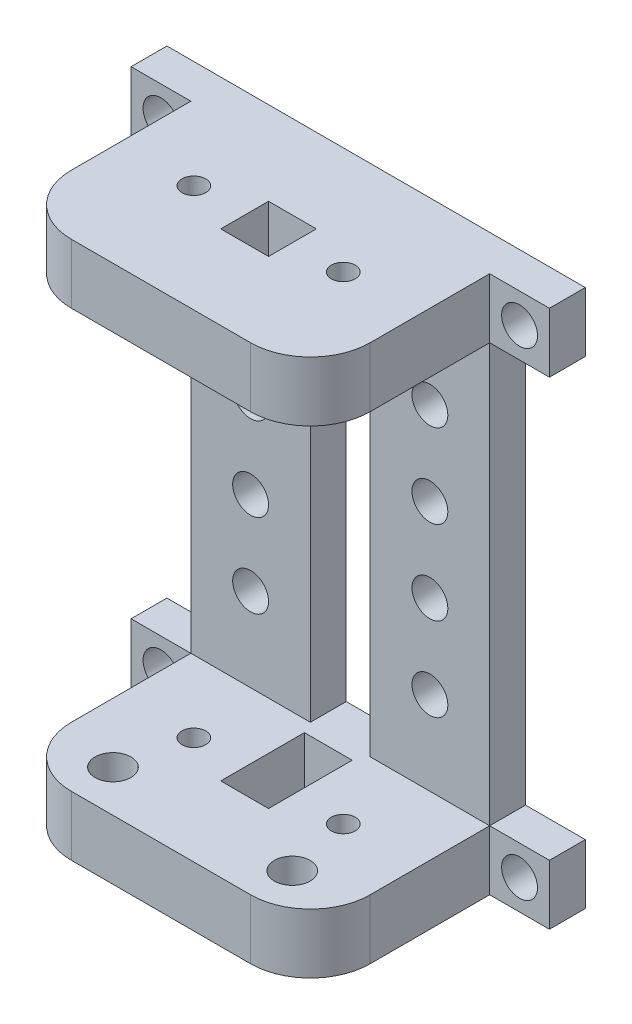
SolidWorks part; units mm, degrees
ref_plane "Plano frontal" through (0, 0, 0) normal (0, 0, 1) x (1, 0, 0)
ref_plane "Plano superior" through (0, 0, 0) normal (0, 1, 0) x (1, 0, 0)
ref_plane "Plano direito" through (0, 0, 0) normal (1, 0, 0) x (0, 0, -1)
sketch "Esboço1" plane through (0, 0, 0) normal (0, 0, 1) x (1, 0, 0)
  line L0 (-24.4304, 7.0667) -> (10.5696, 7.0667)
  line L1 (-24.4304, 7.0667) -> (-24.4304, 2.0667)
  line L2 (10.5696, -37.9333) -> (-24.4304, -37.9333)
  line L3 (-24.4304, 2.0667) -> (-19.4304, 2.0667)
  line L4 (-19.4304, 2.0667) -> (-19.4304, -32.9333)
  line L5 (-19.4304, -32.9333) -> (-24.4304, -32.9333)
  line L6 (-24.4304, -32.9333) -> (-24.4304, -37.9333)
  line L7 (10.5696, -37.9333) -> (10.5696, -32.9333)
  line L8 (10.5696, -32.9333) -> (5.5696, -32.9333)
  line L9 (5.5696, -32.9333) -> (5.5696, 2.0667)
  line L10 (5.5696, 2.0667) -> (10.5696, 2.0667)
  line L11 (10.5696, 2.0667) -> (10.5696, 7.0667)
  line L12 (-9.4304, 2.0667) -> (-9.4304, -32.9333)
  line L13 (-9.4304, -32.9333) -> (-4.4304, -32.9333)
  line L14 (-4.4304, -32.9333) -> (-4.4304, 2.0667)
  line L15 (-4.4304, 2.0667) -> (-9.4304, 2.0667)
  circle A0 centre (-14.4304, -4.9333) radius 1.5
  circle A1 centre (-14.4304, -11.9333) radius 1.5
  circle A2 centre (-14.4304, -18.9333) radius 1.5
  circle A3 centre (0.5696, -4.9333) radius 1.5
  circle A4 centre (0.5696, -18.9333) radius 1.5
  circle A5 centre (0.5696, -25.9333) radius 1.5
  circle A6 centre (-14.4304, -25.9333) radius 1.5
  circle A7 centre (0.5696, -11.9333) radius 1.5
  circle A8 centre (-21.9304, 4.5667) radius 1.5
  circle A9 centre (8.0696, 4.5667) radius 1.5
  circle A10 centre (-21.9304, -35.4333) radius 1.5
  circle A11 centre (8.0696, -35.4333) radius 1.5
  dimension "D13" = 3
  dimension "D1" = 35
  dimension "D2" = 10
  dimension "D3" = 10
  dimension "D4" = 5
  dimension "D5" = 5
  dimension "D6" = 5
  dimension "D7" = 5
  dimension "D8" = 5
  dimension "D9" = 5
  dimension "D10" = 5
  dimension "D11" = 10
  dimension "D12" = 35
  dimension "D14" = 7
  dimension "D15" = 7
  dimension "D16" = 7
  dimension "D17" = 7
  dimension "D18" = 45
  dimension "D19" = 5
  dimension "D20" = 5
  dimension "D21" = 5
  dimension "D22" = 5
  dimension "D23" = 5
  dimension "D24" = 5
  dimension "D25" = 5
  dimension "D26" = 7
  dimension "D27" = 7
  dimension "D28" = 7
  dimension "D29" = 7
  dimension "D30" = 5
  dimension "D31" = 2.5
  dimension "D32" = 2.5
  dimension "D33" = 2.5
  dimension "D34" = 2.5
  dimension "D35" = 2.5
  dimension "D36" = 2.5
  dimension "D37" = 2.5
  dimension "D38" = 2.5
extrude "Ressalto-extrusão1" add sketch "Esboço1" against normal blind 3
sketch "Esboço2" plane through (0, 0, 0) normal (0, 0, 1) x (1, 0, 0)
  line L0 (-19.4304, 2.0667) -> (-19.4304, 7.0667)
  line L1 (10.5696, 7.0667) -> (-24.4304, 7.0667) construction
  line L2 (5.5696, 2.0667) -> (-19.4304, 2.0667)
  line L3 (5.5696, 2.0667) -> (5.5696, 7.0667)
  line L4 (5.5696, 7.0667) -> (-19.4304, 7.0667)
  line L5 (-19.4304, -32.9333) -> (-19.4304, -37.9333)
  line L6 (-24.4304, -37.9333) -> (10.5696, -37.9333) construction
  line L7 (-19.4304, -37.9333) -> (5.5696, -37.9333)
  line L8 (5.5696, -37.9333) -> (5.5696, -32.9333)
  line L9 (5.5696, -32.9333) -> (-19.4304, -32.9333)
extrude "Ressalto-extrusão2" add sketch "Esboço2" along normal blind 15
fillet "Filete5" radius 5 1 edges at (5.5696, -35.4333, 15)
fillet "Filete6" radius 5 1 edges at (-19.4304, -35.4333, 15)
fillet "Filete7" radius 5 2 edges at (-19.4304, 4.5667, 15)
fillet "Filete8" radius 5 2 edges at (5.5696, 4.5667, 15)
sketch "Esboço3" plane through (0, -37.9333, 0) normal (0, -1, 0) x (-1, 0, 0)
  line L5 (8.9304, -8) -> (4.9304, -8)
  line L6 (4.9304, -8) -> (4.9304, -1)
  line L7 (4.9304, -1) -> (8.9304, -1)
  line L8 (8.9304, -1) -> (8.9304, -8)
  line L10 (14.4304, -15) -> (-0.5696, -15) construction
  line L11 (19.4304, -10) -> (19.4304, 0) construction
  circle A0 centre (13.1804, -6) radius 1
  circle A1 centre (0.6804, -6) radius 1
  circle A2 centre (14.4304, -11.5169) radius 1.5
  circle A3 centre (-0.5696, -11.5169) radius 1.5
  dimension "D7" = 2
  dimension "D8" = 2
  dimension "D9" = 5
  dimension "D10" = 3
  dimension "D1" = 7
  dimension "D2" = 4
  dimension "D3" = 7
  dimension "D4" = 9
  dimension "D5" = 9
  dimension "D6" = 5
sketch "Esboço4" plane through (0, 7.0667, 0) normal (0, 1, 0) x (1, 0, 0)
  line L0 (-8.9304, -4) -> (-8.9304, -8)
  line L1 (-8.9304, -8) -> (-4.9304, -8)
  line L2 (-4.9304, -8) -> (-4.9304, -4)
  line L3 (-4.9304, -4) -> (-8.9304, -4)
  line L4 (10.5696, 3) -> (-24.4304, 3) construction
  line L6 (-19.4304, -10) -> (-19.4304, 0) construction
  line L7 (5.5696, -10) -> (5.5696, 0) construction
  circle A0 centre (-13.1804, -6) radius 1
  circle A1 centre (-0.6804, -6) radius 1
  dimension "D1" = 2
  dimension "D2" = 9
  dimension "D3" = 9
  dimension "D4" = 6.25
  dimension "D5" = 6.25
  dimension "D6" = 10.5
  dimension "D7" = 7
  dimension "D8" = 4
  dimension "D9" = 4
extrude "Corte-extrusão2" cut sketch "Esboço4" against normal blind 5
extrude "Corte-extrusão3" cut sketch "Esboço3" against normal blind 5
